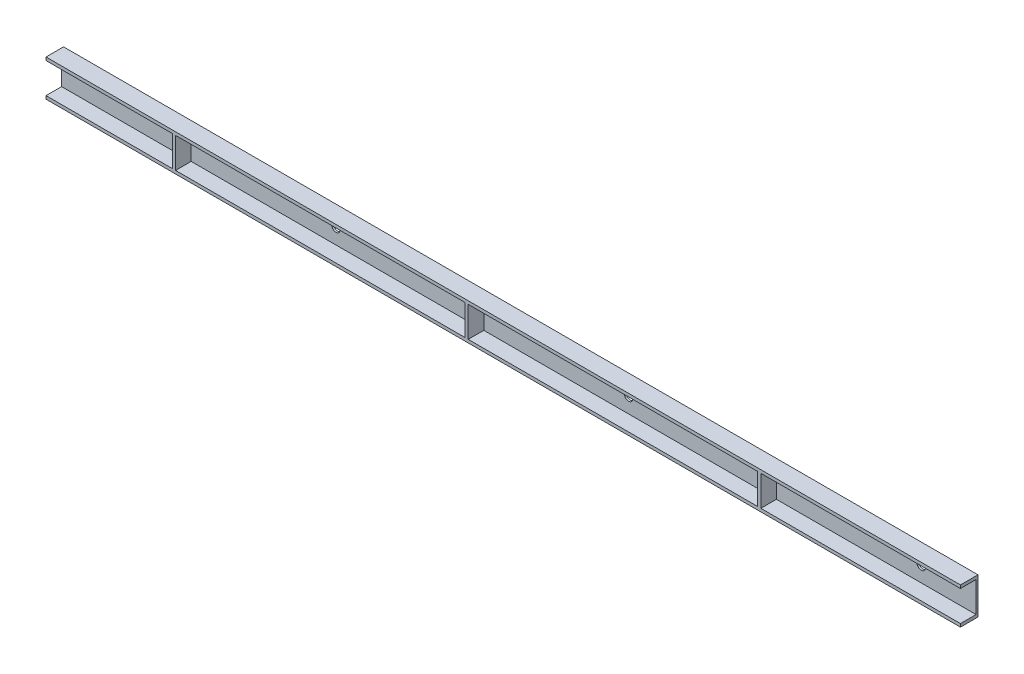
SolidWorks part; units mm, degrees
ref_plane "前视基准面" through (0, 0, 0) normal (0, 0, 1) x (1, 0, 0)
ref_plane "上视基准面" through (0, 0, 0) normal (0, 1, 0) x (1, 0, 0)
ref_plane "右视基准面" through (0, 0, 0) normal (1, 0, 0) x (0, 0, -1)
sketch "草图1" plane through (0, 0, 0) normal (0, 0, 1) x (1, 0, 0)
  line L1 (0, 0) -> (4300, 0)
  line L2 (0, 0) -> (0, 100)
  line L3 (0, 100) -> (4300, 100)
  line L4 (4300, 0) -> (4300, 100)
  dimension "D1" = 4300
  dimension "D2" = 100
extrude "拉伸1" add sketch "草图1" along normal blind 48
sketch "草图2" plane through (0, 0, 48) normal (0, 0, 1) x (1, 0, 0)
  line L0 (0, 100) -> (0, 0) construction
  line L1 (0, 91.5) -> (4300, 91.5)
  line L2 (0, 91.5) -> (0, 8.5)
  line L3 (0, 8.5) -> (4300, 8.5)
  line L4 (4300, 91.5) -> (4300, 8.5)
  line L5 (4300, 100) -> (0, 100) construction
  line L6 (0, 0) -> (4300, 0) construction
  line L7 (4300, 0) -> (4300, 100) construction
  dimension "D1" = 8.5
  dimension "D2" = 8.5
extrude "拉伸2" cut sketch "草图2" against normal blind 42.7
sketch "草图3" plane through (0, 0, 5.3) normal (0, 0, 1) x (1, 0, 0)
  line L0 (4300, 91.5) -> (0, 91.5) construction
  line L1 (545.75, 91.5) -> (554.25, 91.5)
  line L2 (545.75, 91.5) -> (545.75, 8.5)
  line L3 (545.75, 8.5) -> (554.25, 8.5)
  line L4 (554.25, 91.5) -> (554.25, 8.5)
  line L5 (0, 8.5) -> (4300, 8.5) construction
  line L6 (550, 91.5) -> (550, 8.5) construction
  line L7 (0, 91.5) -> (0, 8.5) construction
  dimension "D1" = 8.5
  dimension "D2" = 550
extrude "拉伸3" add sketch "草图3" along normal blind 42.7
pattern_linear "阵列(线性)1" count 5 spacing 800 along (1, 0, 0) of "拉伸3"
sketch "草图4" plane through (0, 0, 0) normal (0, 0, -1) x (-1, 0, 0)
  line L0 (-4300, 50) -> (0, 50) construction
  line L1 (-4300, 0) -> (-4300, 100) construction
  line L2 (0, 100) -> (0, 0) construction
  circle A0 centre (-4150, 50) radius 11.5
  dimension "D1" = 23
  dimension "D2" = 150
extrude "拉伸4" cut sketch "草图4" against normal through all
pattern_linear "阵列(线性)2" count 6 spacing 800 along (-1, 0, 0) of "拉伸4"
sketch "草图5" plane through (0, 0, 0) normal (0, 0, -1) x (-1, 0, 0)
  line L0 (0, 0) -> (-4300, 0) construction
  line L1 (0, 100) -> (-1800, 100)
  line L2 (0, 100) -> (0, 0)
  line L3 (0, 0) -> (-1800, 0)
  line L4 (-1800, 100) -> (-1800, 0)
  dimension "D1" = 1800
extrude "切除-拉伸1" cut sketch "草图5" against normal blind 48
